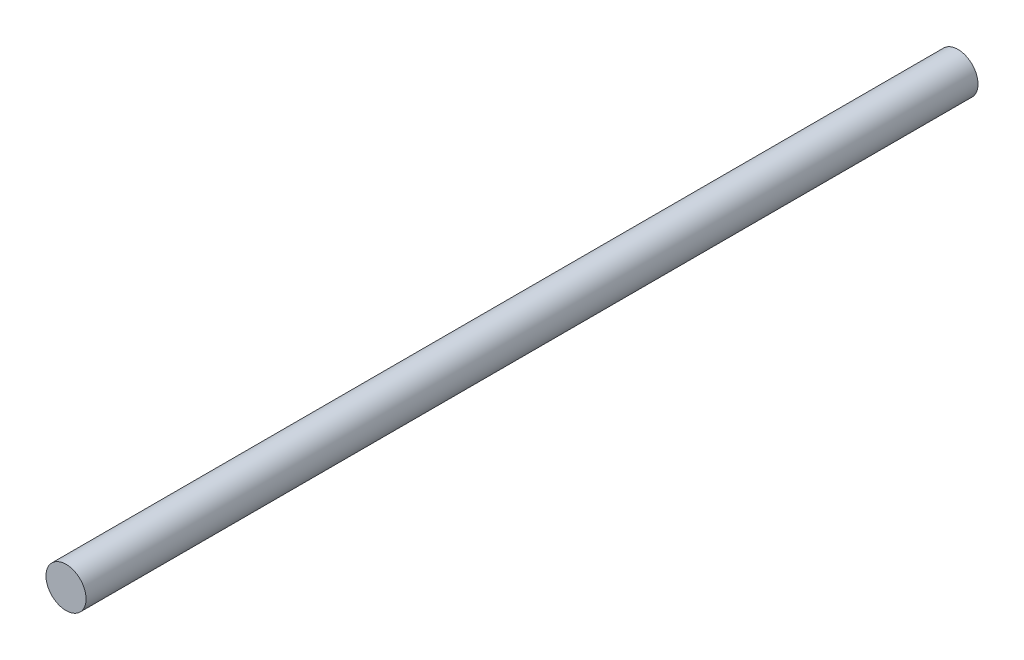
SolidWorks part; units mm, degrees
ref_plane "Front Plane" through (0, 0, 0) normal (0, 0, 1) x (1, 0, 0)
ref_plane "Top Plane" through (0, 0, 0) normal (0, 1, 0) x (1, 0, 0)
ref_plane "Right Plane" through (0, 0, 0) normal (1, 0, 0) x (0, 0, -1)
sketch "Sketch1" plane through (0, 0, 0) normal (0, 0, 1) x (1, 0, 0)
  circle A0 centre (0, 0) radius 2.25
  dimension "D1" = 4.5
extrude "Boss-Extrude1" add sketch "Sketch1" along normal blind 100
